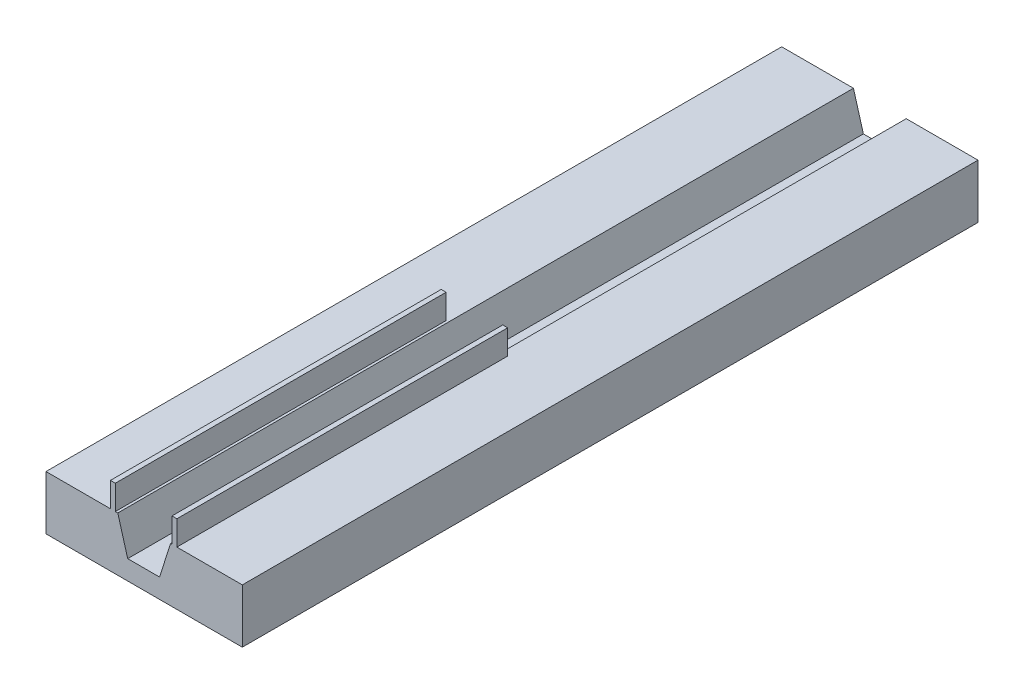
SolidWorks part; units mm, degrees
ref_plane "Alzado" through (0, 0, 0) normal (0, 0, 1) x (1, 0, 0)
ref_plane "Planta" through (0, 0, 0) normal (0, 1, 0) x (1, 0, 0)
ref_plane "Vista lateral" through (0, 0, 0) normal (1, 0, 0) x (0, 0, -1)
sketch "Croquis1" plane through (0, 0, 0) normal (0, 0, 1) x (1, 0, 0)
  line L0 (-6.5, 0) -> (6.5, 0)
  line L2 (6.5, 0) -> (10.9569, 14.1)
  line L3 (-10.5431, 14.1) -> (-6.5, 0)
  line L4 (-39.7931, 14.1) -> (-10.5431, 14.1)
  line L5 (10.9569, 14.1) -> (40.2069, 14.1)
  line L6 (-39.7931, 14.1) -> (-39.7931, -7.9)
  line L7 (-39.7931, -7.9) -> (40.2069, -7.9)
  line L8 (40.2069, -7.9) -> (40.2069, 14.1)
  point P4 (0, 0)
  dimension "D1" = 14.1
  dimension "D2" = 13
  dimension "D3" = 21.5
  dimension "D4" = 74
  dimension "D5" = 80
  dimension "D6" = 22
extrude "Saliente-Extruir1" add sketch "Croquis1" against normal blind 299.79
sketch "Croquis2" plane through (0, 0, 0) normal (0, 0, 1) x (1, 0, 0)
  line L0 (-11.5431, 14.1) -> (-11.5431, 24.1)
  line L1 (-10.5431, 14.1) -> (-39.7931, 14.1) construction
  line L2 (-11.5431, 24.1) -> (-13.5431, 24.1)
  line L3 (-13.5431, 24.1) -> (-13.5431, 14.1)
  line L4 (-13.5431, 14.1) -> (-11.5431, 14.1)
  dimension "D1" = 2
  dimension "D2" = 1
  dimension "D3" = 10
extrude "Saliente-Extruir2" add sketch "Croquis2" against normal blind 134.79
mirror "Simetría1" about plane through (0, 0, 0) normal (1, 0, 0) of "Saliente-Extruir2"
